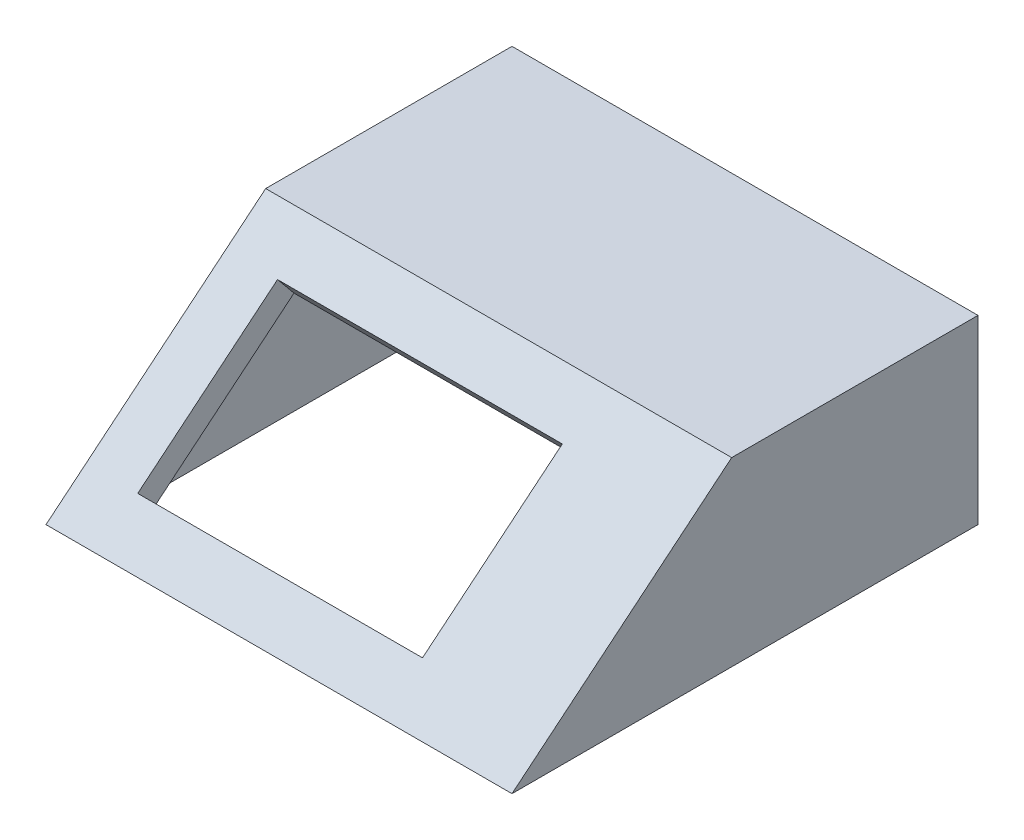
SolidWorks part; units mm, degrees
ref_plane "Front Plane" through (0, 0, 0) normal (0, 0, 1) x (1, 0, 0)
ref_plane "Top Plane" through (0, 0, 0) normal (0, 1, 0) x (1, 0, 0)
ref_plane "Right Plane" through (0, 0, 0) normal (1, 0, 0) x (0, 0, -1)
sketch "Sketch2" plane through (0, 0, 0) normal (1, 0, 0) x (0, 0, -1)
  line L0 (-23.7868, 17.5) -> (-66.2132, -17.5)
  line L1 (-23.7868, -17.5) -> (23.7868, -17.5)
  line L2 (-23.7868, -17.5) -> (-23.7868, 17.5)
  line L3 (-23.7868, 17.5) -> (23.7868, 17.5)
  line L4 (23.7868, -17.5) -> (23.7868, 17.5)
  line L5 (-23.7868, -17.5) -> (23.7868, 17.5) construction
  line L6 (-23.7868, 17.5) -> (23.7868, -17.5) construction
  line L7 (-66.2132, -17.5) -> (-23.7868, -17.5)
  line L8 (-21.9906, 12.5) -> (-58.3561, -17.5)
  line L9 (-21.9906, 12.5) -> (18.7868, 12.5)
  line L10 (18.7868, 12.5) -> (18.7868, -17.5)
  point P0 (0, 0)
  point P9 (0, 0)
  point P12 (-23.7868, 12.5614)
  dimension "D1" = 55
  dimension "D2" = 90
  dimension "D3" = 35
  dimension "D4" = 5
  dimension "D5" = 5
  dimension "D6" = 5
extrude "Boss-Extrude1" add sketch "Sketch2" against normal blind 90 contours L0 L7 L2 | L1 L4 L3 L2 | L10 L9 L8 L2 L1 | L2 L8 L7
ref_plane "Plane1" through (-45, 0, 0) normal (-1, 0, 0) x (0, 0, 1)
sketch "Sketch3" plane through (-45, 0, 0) normal (-1, 0, 0) x (0, 0, 1)
  line L0 (-18.7868, -17.5) -> (-18.7868, 12.5)
  line L1 (66.2132, -17.5) -> (-23.7868, -17.5) construction
  line L2 (-18.7868, 12.5) -> (21.9906, 12.5)
  line L3 (21.9906, 12.5) -> (58.3561, -17.5)
  line L4 (58.3561, -17.5) -> (-18.7868, -17.5)
  line L5 (23.7868, 17.5) -> (66.2132, -17.5) construction
  line L6 (-23.7868, -17.5) -> (-23.7868, 17.5) construction
  line L7 (23.7868, 17.5) -> (-23.7868, 17.5) construction
  dimension "D1" = 5
  dimension "D2" = 5
  dimension "D3" = 5
extrude "Cut-Extrude1" cut sketch "Sketch3" against normal offset from surface 5 and the other way offset from surface (40 mm away) 5 up to face at (0, 0, 10.6066) other way up to face at (-90, 0, 10.6066)
sketch "Sketch4" plane through (0, 22.0898, 18.2231) normal (0, 0.7714, 0.6364) x (1, 0, 0)
  line L0 (-90, -7.2125) -> (-90, -62.2125) construction
  line L1 (-80, -52.2125) -> (-25, -52.2125)
  line L2 (-80, -52.2125) -> (-80, -17.2125)
  line L3 (-80, -17.2125) -> (-25, -17.2125)
  line L4 (-25, -52.2125) -> (-25, -17.2125)
  line L5 (-80, -52.2125) -> (-25, -17.2125) construction
  line L6 (-80, -17.2125) -> (-25, -52.2125) construction
  point P0 (-52.5, -34.7125)
  point P5 (-51.1269, -35.8281)
  point P6 (0, 0)
  point P7 (0, 0)
  point P10 (-90, -34.7125)
  dimension "D1" = 35
  dimension "D2" = 10
  dimension "D3" = 55
extrude "Cut-Extrude2" cut sketch "Sketch4" against normal up to surface (5 mm away) up to face at (-45, -2.5, 40.1733)
equation "\"device_width\"=90"
equation "\"D2@Sketch2\"=\"device_width\""
equation "\"cap_height\"=35"
equation "\"D3@Sketch2\"=\"cap_height\""
equation "\"slant_length\"=55"
equation "\"D1@Sketch2\"=\"slant_length\""
equation "\"cap_length\"=90"
equation "\"D1@Boss-Extrude1\"=\"cap_length\""
equation "\"device_wall\"=5"
equation "\"D1@Sketch3\"=\"device_wall\""
equation "\"D2@Sketch3\"=\"device_wall\""
equation "\"D3@Sketch3\"=\"device_wall\""
equation "\"D1@Cut-Extrude1\"=\"device_wall\""
equation "\"D2@Cut-Extrude1\"=\"device_wall\""
